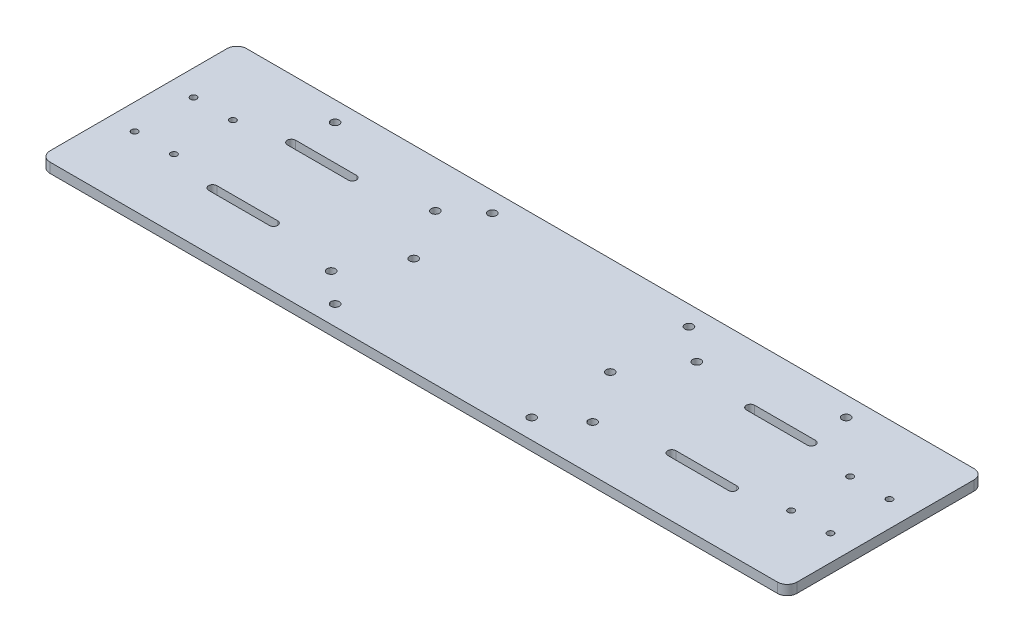
SolidWorks part; units mm, degrees
material "Thornel Mat VMA"
ref_plane "前视基准面" through (0, 0, 0) normal (0, 0, 1) x (1, 0, 0)
ref_plane "上视基准面" through (0, 0, 0) normal (0, 1, 0) x (1, 0, 0)
ref_plane "右视基准面" through (0, 0, 0) normal (1, 0, 0) x (0, 0, -1)
sketch "草图1" plane through (0, 0, 0) normal (0, 1, 0) x (1, 0, 0)
  line L1 (-190, -50) -> (190, -50)
  line L2 (-190, -50) -> (-190, 50)
  line L3 (-190, 50) -> (190, 50)
  line L4 (190, -50) -> (190, 50)
  line L5 (-190, -50) -> (190, 50) construction
  line L6 (-190, 50) -> (190, -50) construction
  point P0 (0, 0)
  dimension "D1" = 380
  dimension "D2" = 100
extrude "凸台-拉伸1" add sketch "草图1" along normal blind 5
fillet "圆角2" radius 5 4 edges at (190, 2.5, 50) (190, 2.5, -50) (-190, 2.5, -50) (-190, 2.5, 50)
sketch "草图2" plane through (0, 5, 0) normal (0, 1, 0) x (1, 0, 0)
  line L0 (190, -45) -> (190, 45) construction
  line L1 (-185, -50) -> (185, -50) construction
  circle A0 centre (177, 15) radius 1.6
  dimension "D1" = 3.2
  dimension "D2" = 13
  dimension "D3" = 65
extrude "切除-拉伸1" cut sketch "草图2" against normal through all
pattern_linear "阵列(线性)1" count 2 spacing 20 along (-1, 0, 0) of "切除-拉伸1"
ref_plane "基准面2" through (0, 0, 0) normal (0, 0, 1) x (1, 0, 0)
ref_plane "基准面3" through (0, 0, 0) normal (1, 0, 0) x (0, 0, -1)
mirror "镜向1" about plane through (0, 0, 0) normal (0, 0, 1) of "阵列(线性)1", "切除-拉伸1"
mirror "镜向2" about plane through (0, 0, 0) normal (1, 0, 0) of "镜向1", "切除-拉伸1", "阵列(线性)1"
sketch "草图3" plane through (0, 5, 0) normal (0, 1, 0) x (1, 0, 0)
  line L0 (185, 50) -> (-185, 50) construction
  line L1 (0, -2.75) -> (0, 2.75) construction
  circle A0 centre (-50, 40) radius 2.1
  dimension "D1" = 4.2
  dimension "D2" = 10
  dimension "D3" = 50
extrude "切除-拉伸2" cut sketch "草图3" against normal through all
pattern_linear "阵列(线性)2" count 3 spacing 40 along (0, 0, 1) of "切除-拉伸2"
mirror "镜向3" about plane through (0, 0, 0) normal (1, 0, 0) of "阵列(线性)2", "切除-拉伸2"
sketch "草图4" plane through (0, 5, 0) normal (0, 1, 0) x (1, 0, 0)
  line L0 (-190, 45) -> (-190, -45) construction
  line L1 (-185, -50) -> (185, -50) construction
  circle A0 centre (-65.5, -26.5) radius 2.1
  dimension "D1" = 4.2
  dimension "D2" = 124.5
  dimension "D3" = 23.5
extrude "切除-拉伸3" cut sketch "草图4" against normal through all
mirror "镜向4" about plane through (0, 0, 0) normal (0, 0, 1) of "切除-拉伸3"
pattern_linear "阵列(线性)3" count 2 spacing 133 along (1, 0, 0) of "镜向4", "切除-拉伸3"
sketch "草图5" plane through (0, 0, 0) normal (0, -1, 0) x (-1, 0, 0)
  line L0 (65.5, 26.5) -> (-67.5, 26.5) construction
pattern_linear "阵列(线性)4" count 2 spacing 80 along (-1, 0, 0) of "切除-拉伸2"
mirror "镜向5" about plane through (0, 0, 0) normal (1, 0, 0) of "阵列(线性)4"
sketch "草图6" plane through (0, 5, 0) normal (0, 1, 0) x (1, 0, 0)
  line L0 (-132.2299, 20.025) -> (-101.2784, 20.025) construction
  line L1 (-132.2299, 22.1103) -> (-101.2784, 22.1103)
  line L2 (-132.2299, 17.9396) -> (-101.2784, 17.9396)
  arc A0 (-132.2299, 22.1103) -> (-132.2299, 17.9396) centre (-132.2299, 20.025) ccw
  arc A1 (-101.2784, 17.9396) -> (-101.2784, 22.1103) centre (-101.2784, 20.025) ccw
  point P2 (-116.7541, 20.025)
extrude "切除-拉伸4" cut sketch "草图6" against normal through all
mirror "镜向6" about plane through (0, 0, 0) normal (0, 0, 1) of "切除-拉伸4"
mirror "镜向7" about plane through (0, 0, 0) normal (1, 0, 0) of "镜向6", "切除-拉伸4"
